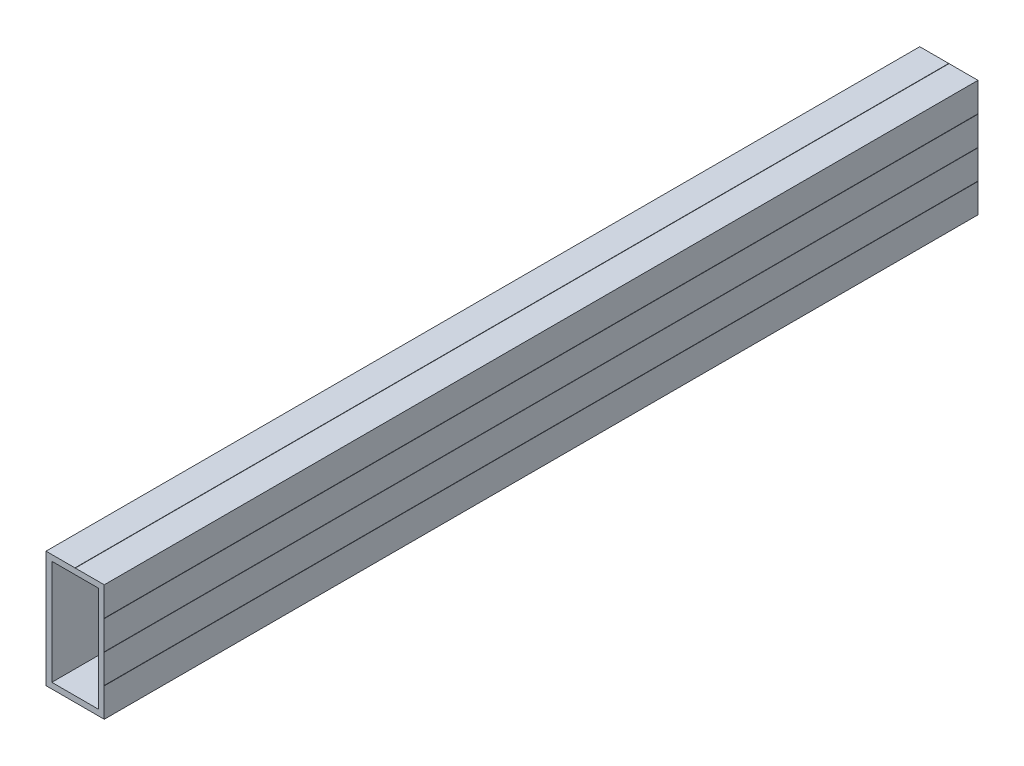
SolidWorks part; units mm, degrees
ref_plane "Front Plane" through (0, 0, 0) normal (0, 0, 1) x (1, 0, 0)
ref_plane "Top Plane" through (0, 0, 0) normal (0, 1, 0) x (1, 0, 0)
ref_plane "Right Plane" through (0, 0, 0) normal (1, 0, 0) x (0, 0, -1)
ref_plane "Plane1" through (12.7, 0, 0) normal (1, 0, 0) x (0, 0, -1)
sketch "Sketch1" plane through (12.7, 0, 0) normal (1, 0, 0) x (0, 0, -1)
  line L0 (-749.3, 25.4) -> (-749.3, -25.4)
  line L1 (-749.3, -25.4) -> (749.3, -25.4)
  line L2 (749.3, -25.4) -> (749.3, 25.4)
  line L3 (749.3, 25.4) -> (-749.3, 25.4)
extrude "Boss-Extrude1" add sketch "Sketch1" against normal blind 25.4
sketch "Sketch2" plane through (0, 0, 749.3) normal (0, 0, 1) x (1, 0, 0)
  line L0 (0.0762, 25.4) -> (-0.0762, 25.4)
  line L1 (-0.0762, 25.4) -> (0.0762, 25.2476)
  line L2 (0.0762, 25.2476) -> (0.0762, 25.4)
extrude "Cut-Extrude1" cut sketch "Sketch2" against normal blind 1498.6
sketch "Sketch3" plane through (0, 0, 749.3) normal (0, 0, 1) x (1, 0, 0)
  line L0 (12.7, 12.6238) -> (12.7, 12.7762)
  line L1 (12.7, 12.7762) -> (12.5476, 12.7762)
  line L2 (12.5476, 12.7762) -> (12.7, 12.6238)
extrude "Cut-Extrude2" cut sketch "Sketch3" against normal through all
sketch "Sketch4" plane through (0, 0, 749.3) normal (0, 0, 1) x (1, 0, 0)
  line L0 (12.7, -0.0762) -> (12.7, 0.0762)
  line L1 (12.7, 0.0762) -> (12.5476, -0.0762)
  line L2 (12.5476, -0.0762) -> (12.7, -0.0762)
extrude "Cut-Extrude3" cut sketch "Sketch4" against normal blind 1498.6
sketch "Sketch5" plane through (0, 0, 749.3) normal (0, 0, 1) x (1, 0, 0)
  line L0 (12.7, -12.7762) -> (12.7, -12.6238)
  line L1 (12.7, -12.6238) -> (12.5476, -12.6238)
  line L2 (12.5476, -12.6238) -> (12.7, -12.7762)
extrude "Cut-Extrude4" cut sketch "Sketch5" against normal blind 1498.6
sketch "Sketch6" plane through (0, 0, 749.3) normal (0, 0, 1) x (1, 0, 0)
  line L0 (0.0762, -25.4) -> (-0.0762, -25.2476)
  line L1 (-0.0762, -25.2476) -> (-0.0762, -25.4)
  line L2 (-0.0762, -25.4) -> (0.0762, -25.4)
extrude "Cut-Extrude5" cut sketch "Sketch6" against normal through all
sketch "Sketch7" plane through (0, 0, 749.3) normal (0, 0, 1) x (1, 0, 0)
  line L0 (-12.7, -12.6238) -> (-12.7, -12.7762)
  line L1 (-12.7, -12.7762) -> (-12.5476, -12.7762)
  line L2 (-12.5476, -12.7762) -> (-12.7, -12.6238)
extrude "Cut-Extrude6" cut sketch "Sketch7" against normal through all
sketch "Sketch8" plane through (0, 0, 749.3) normal (0, 0, 1) x (1, 0, 0)
  line L0 (-12.7, 0.0762) -> (-12.7, -0.0762)
  line L1 (-12.7, -0.0762) -> (-12.5476, 0.0762)
  line L2 (-12.5476, 0.0762) -> (-12.7, 0.0762)
extrude "Cut-Extrude7" cut sketch "Sketch8" against normal blind 1498.6
sketch "Sketch9" plane through (0, 0, 749.3) normal (0, 0, 1) x (1, 0, 0)
  line L0 (-12.7, 12.7762) -> (-12.7, 12.6238)
  line L1 (-12.7, 12.6238) -> (-12.5476, 12.6238)
  line L2 (-12.5476, 12.6238) -> (-12.7, 12.7762)
extrude "Cut-Extrude8" cut sketch "Sketch9" against normal blind 1498.6
sketch "Sketch10" plane through (0, 0, 749.3) normal (0, 0, 1) x (1, 0, 0)
  line L0 (10.16, -22.86) -> (10.16, 22.86)
  line L1 (10.16, 22.86) -> (-10.16, 22.86)
  line L2 (-10.16, 22.86) -> (-10.16, -22.86)
  line L3 (-10.16, -22.86) -> (10.16, -22.86)
extrude "Cut-Extrude9" cut sketch "Sketch10" against normal through all
draft "Draft1" type of draft neutral plane draft angle 45 faces to draft 1 face at (0.0762, 25.3238, 0) neutral plane through (-12.7, 25.4, -749.3) neutral plane normal (0, 1, 0) parameters "D1"=45
draft "Draft2" type of draft neutral plane draft angle 45 faces to draft 1 face at (12.6238, 12.7762, 0) neutral plane through (12.7, 0, 0) neutral plane normal (1, 0, 0) parameters "D1"=45
draft "Draft3" type of draft neutral plane draft angle 45 faces to draft 1 face at (-0.0762, -25.3238, 0) neutral plane through (-12.7, -25.4, 749.3) neutral plane normal (0, -1, 0) parameters "D1"=45
draft "Draft4" type of draft neutral plane draft angle 45 faces to draft 1 face at (-12.6238, -12.7762, 0) neutral plane through (-12.7, 0, 0) neutral plane normal (-1, 0, 0) parameters "D1"=45
draft "Draft5" type of draft neutral plane draft angle 45 faces to draft 2 face at (12.6238, -12.6238, 0) face at (12.6238, 0, 0) neutral plane through (12.7, 0, 0) neutral plane normal (1, 0, 0) parameters "D1"=45
draft "Draft6" type of draft neutral plane draft angle 45 faces to draft 2 face at (-12.6238, 0, 0) face at (-12.6238, 12.6238, 0) neutral plane through (-12.7, 0, 0) neutral plane normal (-1, 0, 0) parameters "D1"=45
sketch "Sketch11" plane through (0, 0, -749.3) normal (0, 0, -1) x (-1, 0, 0)
  line L1 (28.0564, 44.6652) -> (-33.9059, 44.6652)
  line L2 (28.0564, 44.6652) -> (28.0564, -44.0138)
  line L3 (28.0564, -44.0138) -> (-33.9059, -44.0138)
  line L4 (-33.9059, 44.6652) -> (-33.9059, -44.0138)
extrude "Cut-Extrude10" cut sketch "Sketch11" against normal blind 1117.6
